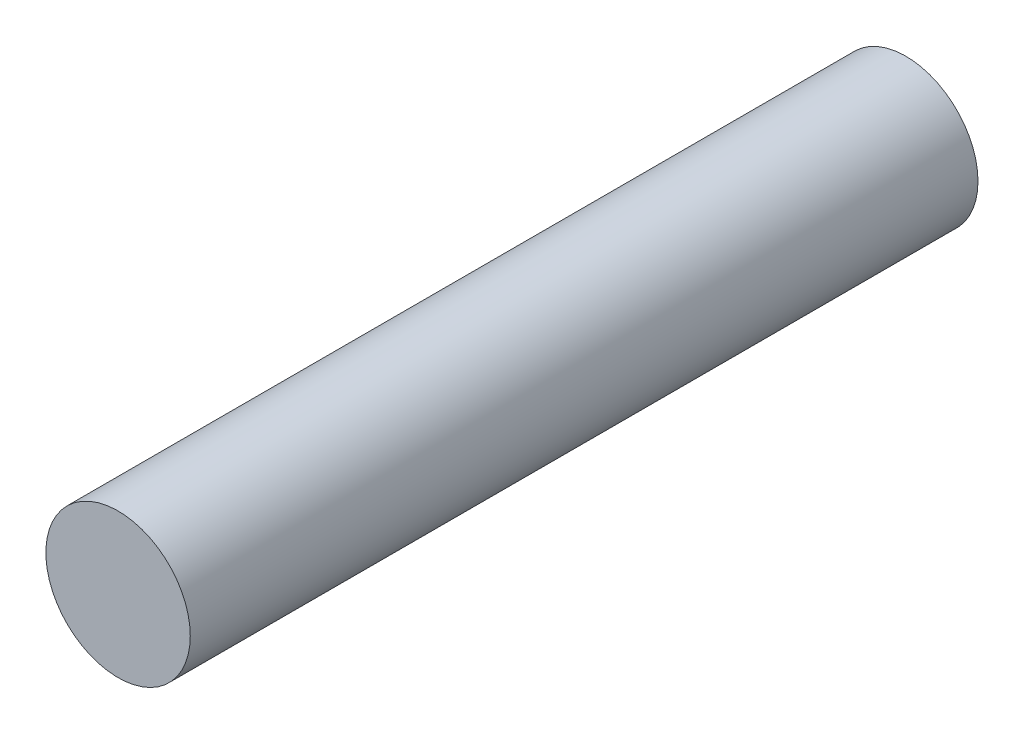
SolidWorks part; units mm, degrees
ref_plane "前视基准面" through (0, 0, 0) normal (0, 0, 1) x (1, 0, 0)
ref_plane "上视基准面" through (0, 0, 0) normal (0, 1, 0) x (1, 0, 0)
ref_plane "右视基准面" through (0, 0, 0) normal (1, 0, 0) x (0, 0, -1)
other "Configuration Table"
sketch "草图1" plane through (0, 0, 0) normal (0, 0, 1) x (1, 0, 0)
  circle A0 centre (0, 0) radius 5.5
  dimension "D1" = 11
extrude "凸台-拉伸1" add sketch "草图1" along normal blind 60
